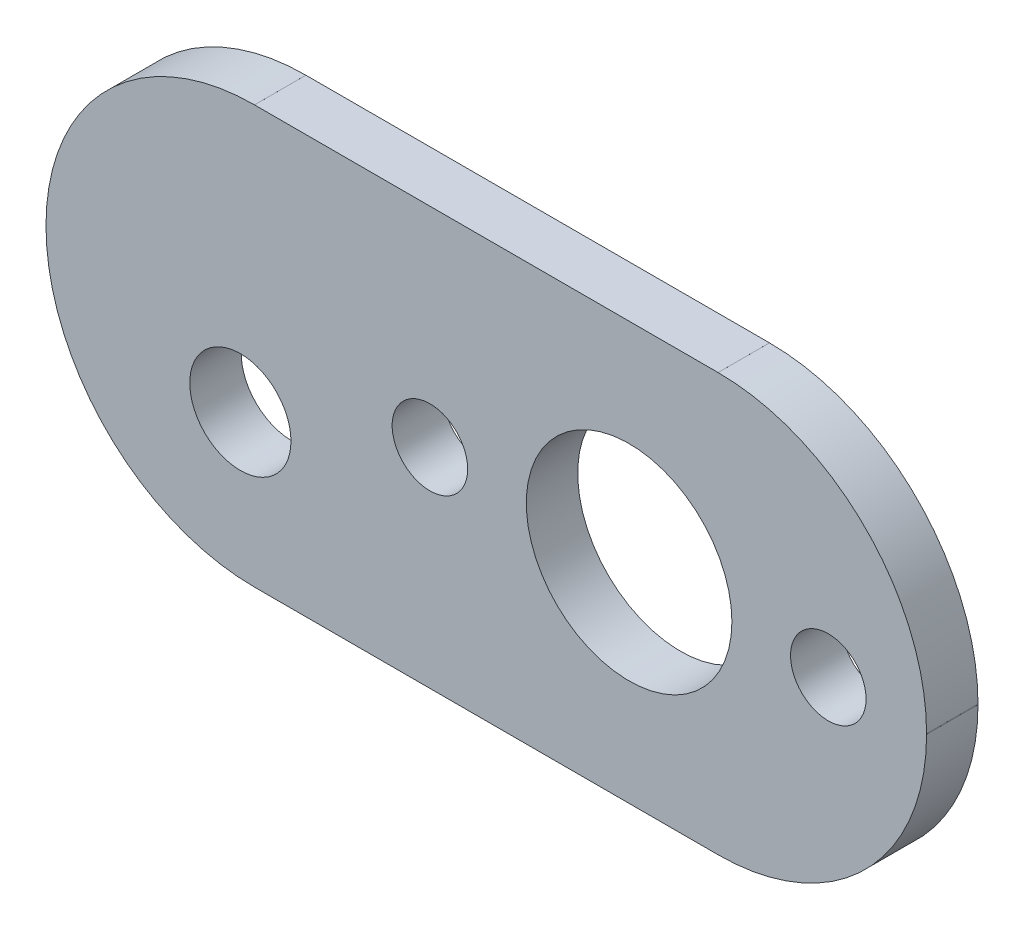
SolidWorks part; units mm, degrees
ref_plane "Alzado" through (0, 0, 0) normal (0, 0, 1) x (1, 0, 0)
ref_plane "Planta" through (0, 0, 0) normal (0, 1, 0) x (1, 0, 0)
ref_plane "Vista lateral" through (0, 0, 0) normal (1, 0, 0) x (0, 0, -1)
sketch "Model" plane through (0, 0, 0) normal (0, 0, 1) x (1, 0, 0)
  line L0 (9.26, 0.01) -> (9.26, -0.01)
  line L1 (2.77, 6.5) -> (-11.66, 6.5)
  line L2 (-18.15, 0.01) -> (-18.15, -0.01)
  line L3 (-11.66, -6.5) -> (2.77, -6.5)
  circle A1 centre (-12.1, -2) radius 1.575
  arc A4 (2.77, -6.5) -> (9.26, -0.01) centre (2.7698, -0.0098) ccw
  arc A5 (2.77, -6.4997) -> (2.77, -6.5003) centre (2.77, -6.5) ccw
  arc A6 (9.2602, -0.01) -> (9.2598, -0.01) centre (9.26, -0.01) ccw
  arc A7 (9.2598, -0.01) -> (9.2602, -0.01) centre (9.26, -0.01) ccw
  arc A8 (9.2602, 0.01) -> (9.2598, 0.01) centre (9.26, 0.01) ccw
  arc A9 (9.26, 0.01) -> (2.77, 6.5) centre (2.7698, 0.0098) ccw
  arc A10 (9.2598, 0.01) -> (9.2602, 0.01) centre (9.26, 0.01) ccw
  arc A11 (2.77, 6.5003) -> (2.77, 6.4997) centre (2.77, 6.5) ccw
  arc A12 (-11.66, 6.5003) -> (-11.66, 6.4997) centre (-11.66, 6.5) ccw
  arc A13 (2.77, 6.4997) -> (2.77, 6.5003) centre (2.77, 6.5) ccw
  arc A14 (-11.66, 6.5) -> (-18.15, 0.01) centre (-11.6598, 0.0098) ccw
  arc A15 (-11.66, 6.4997) -> (-11.66, 6.5003) centre (-11.66, 6.5) ccw
  arc A16 (-18.1503, 0.01) -> (-18.1498, 0.01) centre (-18.1501, 0.01) ccw
  arc A17 (-18.1503, -0.01) -> (-18.1498, -0.01) centre (-18.1501, -0.01) ccw
  arc A18 (-18.1498, 0.01) -> (-18.1503, 0.01) centre (-18.1501, 0.01) ccw
  arc A19 (-18.15, -0.01) -> (-11.66, -6.5) centre (-11.6598, -0.0098) ccw
  arc A20 (-18.1498, -0.01) -> (-18.1503, -0.01) centre (-18.1501, -0.01) ccw
  arc A21 (-11.66, -6.5003) -> (-11.66, -6.4997) centre (-11.66, -6.5) ccw
  arc A22 (2.77, -6.5003) -> (2.77, -6.4997) centre (2.77, -6.5) ccw
  arc A23 (-11.66, -6.4997) -> (-11.66, -6.5003) centre (-11.66, -6.5) ccw
  circle A24 centre (0, 0) radius 3.2
  circle A25 centre (-6.2, 0) radius 1.175
  circle A26 centre (6.2, 0) radius 1.175
  dimension "D3" = 3.15
  dimension "D1" = 6.2
  dimension "D2" = 2
  dimension "D4" = 12.1
  dimension "D5" = 6.2
  dimension "D6" = 6.5
extrude "Saliente-Extruir1" add sketch "Model" along normal blind 1.6 contours A23 A21 L3 A5 A22 A4 A7 A6 L0 A10 A8 A9 A13 A11 L1 A15 A12 A14 A18 A16 L2 A20 A17 A19 A26 A25 A24 A1
equation "\"1.6MMmm\"=10"
